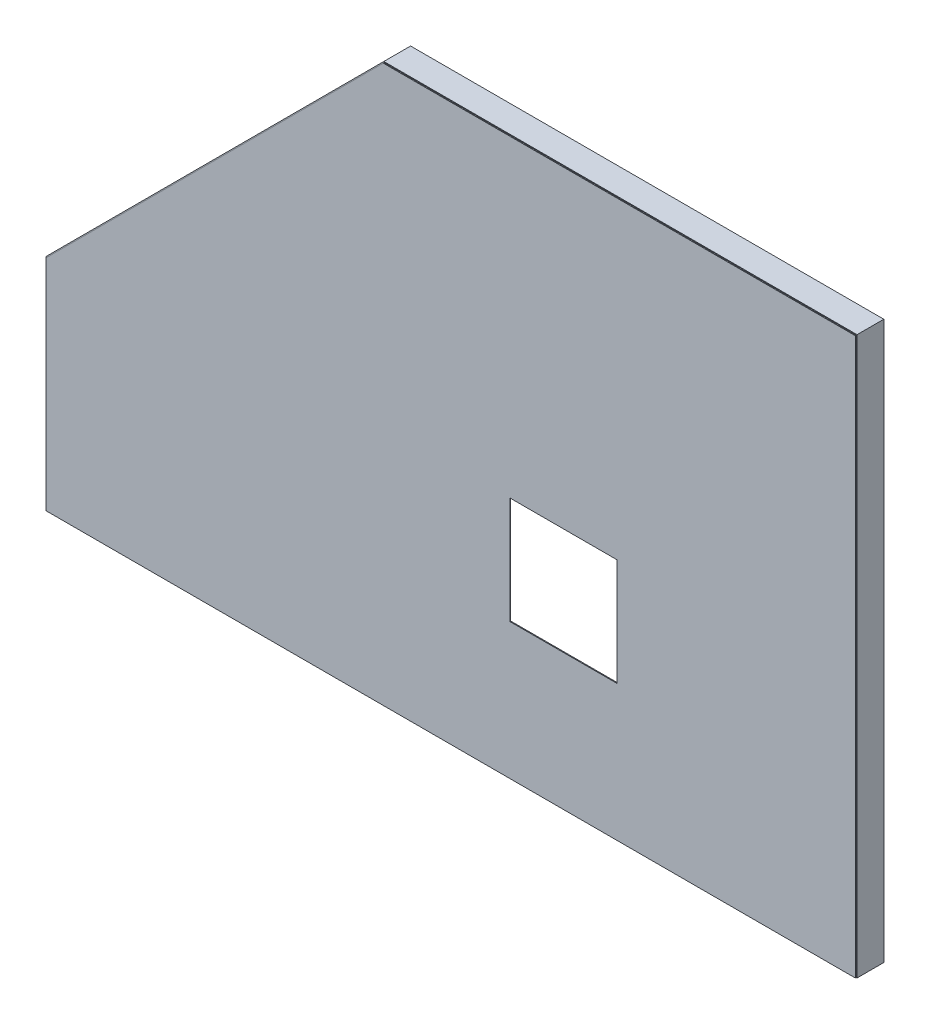
SolidWorks part; units mm, degrees
other "Elemento de detalle1"
other "Elemento de detalle2"
other "Carpeta de soldadura"
other "Cordón de soldadura1"
other "Cordón de soldadura2"
ref_plane "Alzado" through (0, 0, 0) normal (0, 0, 1) x (1, 0, 0)
ref_plane "Planta" through (0, 0, 0) normal (0, 1, 0) x (1, 0, 0)
ref_plane "Vista lateral" through (0, 0, 0) normal (1, 0, 0) x (0, 0, -1)
sketch "Croquis1" plane through (0, 0, 0) normal (0, 0, 1) x (1, 0, 0)
  line L0 (0, 0) -> (768, 0)
  line L1 (768, 0) -> (768, 528)
  line L2 (768, 528) -> (320, 528)
  line L3 (320, 528) -> (0, 208)
  line L4 (0, 208) -> (0, 0)
  dimension "D1" = 768
  dimension "D2" = 528
  dimension "D3" = 448
  dimension "D4" = 208
extrude "Saliente-Extruir1" add sketch "Croquis1" along normal blind 0.8357
sketch "Croquis2" plane through (0, 0, 0.8357) normal (0, 0, 1) x (1, 0, 0)
  line L1 (440.0393, 129.077) -> (541.6393, 129.077)
  line L2 (440.0393, 129.077) -> (440.0393, 230.677)
  line L3 (440.0393, 230.677) -> (541.6393, 230.677)
  line L4 (541.6393, 129.077) -> (541.6393, 230.677)
  dimension "D1" = 101.6
extrude "Cortar-Extruir1" cut sketch "Croquis2" against normal blind 454.8357
sketch "Croquis3" plane through (0, 0, 0) normal (0, 0, -1) x (-1, 0, 0)
  line L0 (0.8357, 0) -> (0.8357, 208.3461)
  line L1 (0.8357, 208.3461) -> (-319.6539, 528.8357)
  line L2 (-319.6539, 528.8357) -> (-768.8357, 528.8357)
  line L3 (-768.8357, 528.8357) -> (-768.8357, 0)
  line L4 (0.8357, 0) -> (0, 0)
  line L5 (0, 0) -> (0, 208)
  line L6 (0, 208) -> (-320, 528)
  line L7 (-320, 528) -> (-768, 528)
  line L8 (-768, 528) -> (-768, 0)
  line L9 (-768, 0) -> (0, 0)
  line L10 (0, 0) -> (0, 208)
  line L11 (0, 208) -> (-320, 528)
  line L12 (-320, 528) -> (-768, 528)
  line L13 (-768, 528) -> (-768, 0)
  line L15 (-768.8357, 0) -> (-768, 0)
  dimension "D1" = 0
  dimension "D2" = 0.8357
extrude "Saliente-Extruir2" add sketch "Croquis3" along normal blind 25.4 separate body
